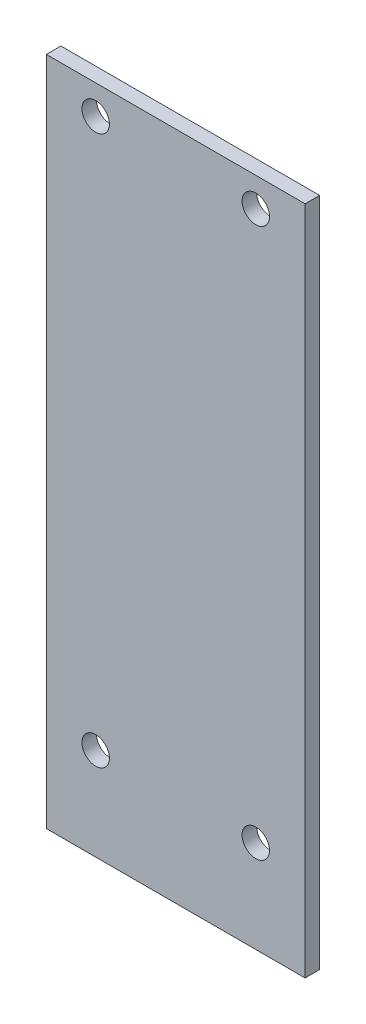
SolidWorks part; units mm, degrees
material "ABS"
ref_plane "X-Y Datum" through (0, 0, 0) normal (0, 0, 1) x (1, 0, 0)
ref_plane "X-Z Datum" through (0, 0, 0) normal (0, 1, 0) x (1, 0, 0)
ref_plane "Y-Z Datum" through (0, 0, 0) normal (1, 0, 0) x (0, 0, -1)
sketch "Sketch1" plane through (0, 0, 0) normal (0, 0, 1) x (1, 0, 0)
  line L1 (-28.275, 73.275) -> (28.275, 73.275)
  line L2 (-28.275, 73.275) -> (-28.275, -73.275)
  line L3 (-28.275, -73.275) -> (28.275, -73.275)
  line L4 (28.275, 73.275) -> (28.275, -73.275)
  line L5 (-28.275, 73.275) -> (28.275, -73.275) construction
  line L6 (-28.275, -73.275) -> (28.275, 73.275) construction
  point P0 (0, 0)
  dimension "D1" = 56.55
  dimension "D2" = 146.55
extrude "Boss-Extrude1" add sketch "Sketch1" along normal blind 3.175
sketch "Sketch2" plane through (0, 0, 3.175) normal (0, 0, 1) x (1, 0, 0)
  circle A0 centre (17.5, -53.075) radius 3 construction
  circle A1 centre (-17.5, -53.075) radius 3 construction
  circle A2 centre (-17.5, 66.925) radius 3 construction
  circle A3 centre (17.5, 66.925) radius 3 construction
  circle A4 centre (17.5, -53.075) radius 3
  circle A5 centre (-17.5, -53.075) radius 3
  circle A6 centre (-17.5, 66.925) radius 3
  circle A7 centre (17.5, 66.925) radius 3
extrude "Cut-Extrude1" cut sketch "Sketch2" against normal through all
